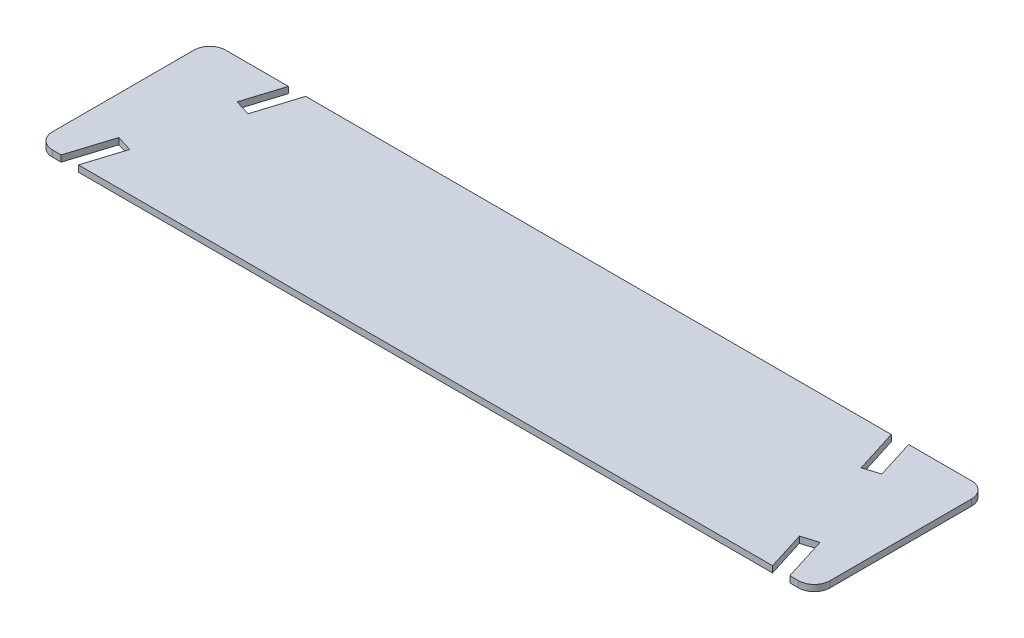
SolidWorks part; units mm, degrees
material "Acrylic (Medium-high impact)"
ref_plane "Front Plane" through (0, 0, 0) normal (0, 0, 1) x (1, 0, 0)
ref_plane "Top Plane" through (0, 0, 0) normal (0, 1, 0) x (1, 0, 0)
ref_plane "Right Plane" through (0, 0, 0) normal (1, 0, 0) x (0, 0, -1)
sketch "Sketch1" plane through (0, 0, 0) normal (0, 1, 0) x (1, 0, 0)
  line L0 (25, 55) -> (21.1092, 42.598)
  line L1 (5, 0) -> (7.7451, 0)
  line L2 (0, 5) -> (0, 50)
  line L3 (5, 55) -> (25, 55)
  line L4 (13.2474, 0) -> (233.9098, 0)
  line L5 (233.9098, 0) -> (230.019, 12.402)
  line L6 (21.1092, 42.598) -> (26.1184, 41.0264)
  line L7 (30.5023, 55) -> (26.1184, 41.0264)
  line L8 (230.019, 12.402) -> (235.0282, 13.9736)
  line L9 (235.0282, 13.9736) -> (239.4121, 0)
  line L10 (7.7451, 0) -> (12.129, 13.9736)
  line L11 (239.4121, 0) -> (242.1572, 0)
  line L12 (247.1572, 5) -> (247.1572, 50)
  line L13 (12.129, 13.9736) -> (17.1382, 12.402)
  line L14 (17.1382, 12.402) -> (13.2474, 0)
  line L15 (242.1572, 55) -> (222.1572, 55)
  line L16 (222.1572, 55) -> (226.048, 42.598)
  line L17 (226.048, 42.598) -> (221.0388, 41.0264)
  line L18 (221.0388, 41.0264) -> (216.6549, 55)
  line L19 (216.6549, 55) -> (30.5023, 55)
  line L20 (123.5786, 55) -> (123.5786, 0) construction
  line L21 (0, 27.5) -> (247.1572, 27.5) construction
  line L22 (26.1184, 41.0264) -> (26.1184, 27.5) construction
  line L23 (12.129, 13.9736) -> (12.129, 27.5) construction
  arc A0 (242.1572, 0) -> (247.1572, 5) centre (242.1572, 5) ccw
  arc A1 (247.1572, 50) -> (242.1572, 55) centre (242.1572, 50) ccw
  arc A2 (5, 0) -> (0, 5) centre (5, 5) cw
  arc A3 (0, 50) -> (5, 55) centre (5, 50) cw
  point P5 (23.6138, 41.8122)
  point P22 (0, 0)
  point P25 (0, 55)
  point P38 (14.6336, 13.1878)
  point P39 (232.5236, 13.1878)
  dimension "D3" = 5
  dimension "D8" = 5
  dimension "D1" = 5.25
  dimension "D2" = 17.418
  dimension "D4" = 217.89
  dimension "D5" = 30
  dimension "D6" = 55
  dimension "D7" = 20
extrude "Boss-Extrude1" add sketch "Sketch1" along normal blind 2
